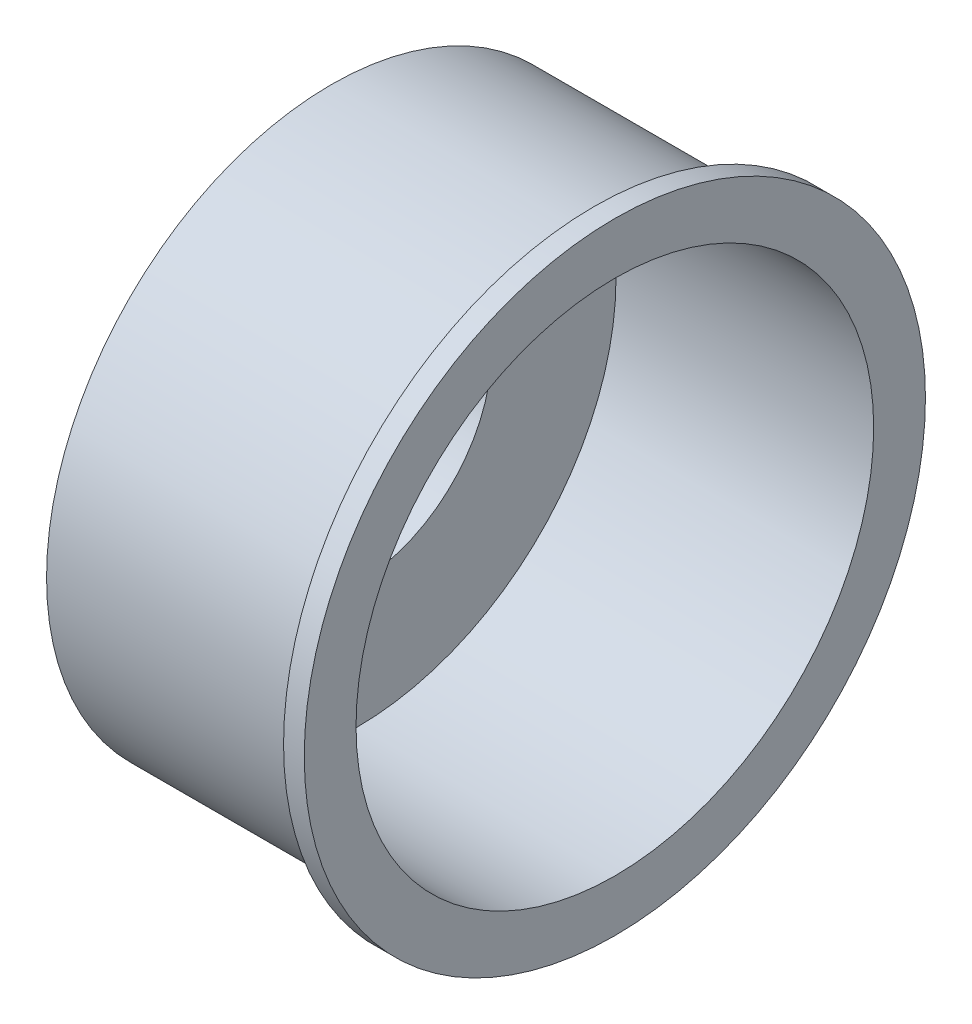
SolidWorks part; units mm, degrees
ref_plane "Front Plane" through (0, 0, 0) normal (0, 0, 1) x (1, 0, 0)
ref_plane "Top Plane" through (0, 0, 0) normal (0, 1, 0) x (1, 0, 0)
ref_plane "Right Plane" through (0, 0, 0) normal (1, 0, 0) x (0, 0, -1)
sketch "Sketch2" plane through (0, 0, 0) normal (0, 0, 1) x (1, 0, 0)
  line L0 (0, 55) -> (0, 26)
  line L1 (0, 55) -> (50.7843, 55)
  line L3 (54.7843, 50) -> (5, 50)
  line L4 (5, 50) -> (5, 26)
  line L5 (5, 26) -> (0, 26)
  line L8 (54.7843, 50) -> (54.7843, 60)
  line L9 (54.7843, 60) -> (50.7843, 60)
  line L10 (50.7843, 60) -> (50.7843, 55)
  line L11 (-500, 0) -> (500, 0) construction
  line L12 (0, 55) -> (0, 26) construction
  line L13 (0, 0) -> (0, 67.7882) construction
  point P13 (0, 0)
  point P14 (0, 0)
  dimension "D1" = 55
  dimension "H" = 54.7843
  dimension "D2" = 26
  dimension "D3" = 5
  dimension "D4" = 5
  dimension "D5" = 4
  dimension "D6" = 1000
  dimension "D7" = 50
revolve "Revolve2" add sketch "Sketch2" angle 360 about L11
equation "\"H\"=54.7843"
equation "\"R_in\"=-10"
equation "\"R_out\"=48.4031"
equation "\"R_AS5600\"=19.1777"
equation "\"D_dayBLDC\"=2.16867"
equation "\"H_day\"=7.07886"
equation "\"D_taibat\"=6.33336"
equation "\"H_taibat\"=3.64778"
